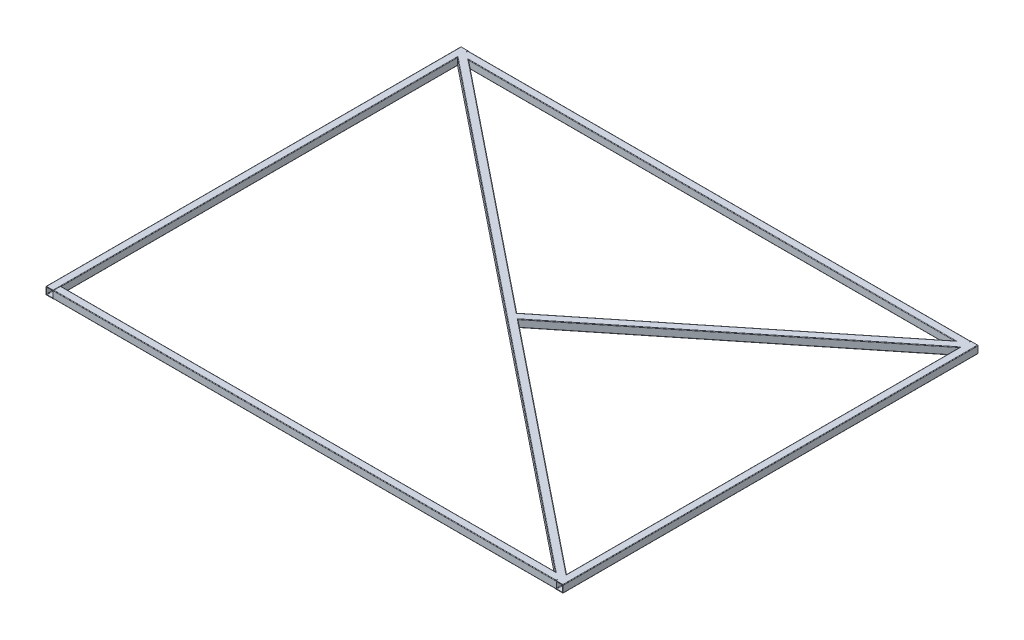
SolidWorks part; units mm, degrees
material "ASTM A500 Grade B"
ref_plane "Front Plane" through (0, 0, 0) normal (0, 0, 1) x (1, 0, 0)
ref_plane "Top Plane" through (0, 0, 0) normal (0, 1, 0) x (1, 0, 0)
ref_plane "Right Plane" through (0, 0, 0) normal (1, 0, 0) x (0, 0, -1)
sketch "Sketch1" plane through (0, 0, 0) normal (0, 1, 0) x (1, 0, 0)
  line L0 (1325, 0) -> (1325, -2125) construction
  line L1 (0, 0) -> (2650, 0)
  line L2 (0, 0) -> (0, -2125)
  line L3 (0, -2125) -> (2650, -2125)
  line L4 (2650, 0) -> (2650, -2125)
  line L5 (0, -1062.5) -> (2650, -1062.5) construction
  line L9 (0, 0) -> (2650, -2125) construction
  line L10 (2650, -2125) -> (2646.4748, -2133.2245) construction
  line L11 (1325, -1062.5) -> (1175.9048, -1248.4305) construction
  line L12 (2650, 0) -> (0, -2125) construction
  line L13 (1325, -1062.5) -> (1281.7828, -1008.6056) construction
  dimension "D1" = 2650
  dimension "D2" = 2125
sketch "Sketch2" plane through (0, 0, 0) normal (0, 0, 1) x (1, 0, 0)
  line L0 (5.3086, 16.1668) -> (32.7914, 16.1668)
  line L1 (2.54, 18.9354) -> (35.56, 18.9354)
  line L2 (0, 16.3954) -> (0, -16.6246)
  line L3 (2.54, -19.1646) -> (35.56, -19.1646)
  line L4 (38.1, 16.3954) -> (38.1, -16.6246)
  line L5 (35.3314, 13.6268) -> (35.3314, -13.856)
  line L6 (5.3086, -16.396) -> (32.7914, -16.396)
  line L7 (2.7686, 13.6268) -> (2.7686, -13.856)
  line L8 (2.7686, 16.1668) -> (2.7686, -16.396) construction
  line L9 (2.7686, -16.396) -> (35.3314, -16.396) construction
  line L10 (35.3314, 16.1668) -> (35.3314, -16.396) construction
  line L11 (38.1, 18.9354) -> (38.1, -19.1646) construction
  line L12 (0, -19.1646) -> (38.1, -19.1646) construction
  line L13 (0, 18.9354) -> (0, -19.1646) construction
  line L14 (0, 18.9354) -> (38.1, 18.9354) construction
  line L15 (2.7686, 16.1668) -> (35.3314, 16.1668) construction
  arc A0 (2.7686, -13.856) -> (5.3086, -16.396) centre (5.3086, -13.856) ccw
  arc A1 (32.7914, -16.396) -> (35.3314, -13.856) centre (32.7914, -13.856) ccw
  arc A2 (38.1, -16.6246) -> (35.56, -19.1646) centre (35.56, -16.6246) cw
  arc A3 (2.54, -19.1646) -> (0, -16.6246) centre (2.54, -16.6246) cw
  arc A4 (0, 16.3954) -> (2.54, 18.9354) centre (2.54, 16.3954) cw
  arc A5 (38.1, 16.3954) -> (35.56, 18.9354) centre (35.56, 16.3954) ccw
  arc A6 (35.3314, 13.6268) -> (32.7914, 16.1668) centre (32.7914, 13.6268) ccw
  arc A7 (2.7686, 13.6268) -> (5.3086, 16.1668) centre (5.3086, 13.6268) cw
  point P17 (38.1, -19.1646)
  dimension "D4" = 2.54
  dimension "D3" = 2.7686
extrude "Boss-Extrude1" add sketch "Sketch2" along normal up to vertex (2125 mm away) up to point (0, 0, 2125)
ref_plane "Plane1" through (1325, 0, 0) normal (-1, 0, 0) x (0, 0, 1)
mirror "Mirror2" about plane through (1325, 0, 0) normal (-1, 0, 0) of bodies 101
sketch "Sketch3" plane through (2611.9, 0, 0) normal (-1, 0, 0) x (0, 0, 1)
  line L0 (2125, -19.1646) -> (0, -19.1646) construction
  line L1 (2.54, 18.9354) -> (35.56, 18.9354)
  line L2 (0, 16.3954) -> (0, -16.6246)
  line L3 (2.54, -19.1646) -> (35.56, -19.1646)
  line L4 (38.1, 16.3954) -> (38.1, -16.6246)
  line L5 (5.3086, 16.1668) -> (32.7914, 16.1668)
  line L6 (35.3314, 13.6268) -> (35.3314, -13.856)
  line L7 (5.3086, -16.396) -> (32.7914, -16.396)
  line L8 (2.7686, 13.6268) -> (2.7686, -13.856)
  line L9 (38.1, 18.9354) -> (38.1, -19.1646) construction
  line L10 (0, -19.1646) -> (38.1, -19.1646) construction
  line L11 (2.7686, -16.396) -> (35.3314, -16.396) construction
  line L12 (35.3314, 16.1668) -> (35.3314, -16.396) construction
  line L13 (2.7686, 16.1668) -> (2.7686, -16.396) construction
  line L14 (0, 18.9354) -> (0, -19.1646) construction
  line L15 (2.7686, 16.1668) -> (35.3314, 16.1668) construction
  line L16 (0, 18.9354) -> (38.1, 18.9354) construction
  arc A0 (38.1, -16.6246) -> (35.56, -19.1646) centre (35.56, -16.6246) cw
  arc A1 (32.7914, -16.396) -> (35.3314, -13.856) centre (32.7914, -13.856) ccw
  arc A2 (5.3086, -16.396) -> (2.7686, -13.856) centre (5.3086, -13.856) cw
  arc A3 (2.54, -19.1646) -> (0, -16.6246) centre (2.54, -16.6246) cw
  arc A4 (2.7686, 13.6268) -> (5.3086, 16.1668) centre (5.3086, 13.6268) cw
  arc A5 (0, 16.3954) -> (2.54, 18.9354) centre (2.54, 16.3954) cw
  arc A6 (38.1, 16.3954) -> (35.56, 18.9354) centre (35.56, 16.3954) ccw
  arc A7 (35.3314, 13.6268) -> (32.7914, 16.1668) centre (32.7914, 13.6268) ccw
  point P14 (38.1, -19.1646)
  dimension "D3" = 2.54
  dimension "D2" = 2.7686
extrude "Boss-Extrude2" add sketch "Sketch3" along normal up to surface (2573.8 mm away) up to face at (38.1, -0.1146, 1062.5)
ref_plane "Plane2" through (0, 0, 1062.5) normal (0, 0, 1) x (1, 0, 0)
mirror "Mirror3" about plane through (0, 0, 1062.5) normal (0, 0, 1) of "Boss-Extrude2"
ref_plane "Plane8" through (1325, 0, 1062.5) normal (-0.7802, 0, -0.6256) x (-0.6256, 0, 0.7802)
sketch "Sketch8" plane through (1325, 0, 1062.5) normal (-0.7802, 0, -0.6256) x (-0.6256, 0, 0.7802)
  line L1 (-16.51, 18.9354) -> (16.51, 18.9354)
  line L2 (-19.05, 16.3954) -> (-19.05, -16.6246)
  line L3 (-16.51, -19.1646) -> (16.51, -19.1646)
  line L4 (19.05, 16.3954) -> (19.05, -16.6246)
  line L6 (16.2814, 13.6268) -> (16.2814, -13.856)
  line L7 (-13.7414, -16.396) -> (13.7414, -16.396)
  line L8 (-16.2814, 13.6268) -> (-16.2814, -13.856)
  line L9 (-13.7414, 16.1668) -> (13.7414, 16.1668)
  line L10 (-19.05, -19.1646) -> (19.05, -19.1646) construction
  line L11 (-19.05, 18.9354) -> (-19.05, -19.1646) construction
  line L12 (-16.2814, -16.396) -> (16.2814, -16.396) construction
  line L13 (-16.2814, 16.1668) -> (-16.2814, -16.396) construction
  line L14 (19.05, 18.9354) -> (19.05, -19.1646) construction
  line L15 (16.2814, 16.1668) -> (16.2814, -16.396) construction
  line L16 (-19.05, 18.9354) -> (19.05, 18.9354) construction
  line L17 (-16.2814, 16.1668) -> (16.2814, 16.1668) construction
  arc A0 (-16.51, -19.1646) -> (-19.05, -16.6246) centre (-16.51, -16.6246) cw
  arc A1 (-13.7414, -16.396) -> (-16.2814, -13.856) centre (-13.7414, -13.856) cw
  arc A2 (16.51, -19.1646) -> (19.05, -16.6246) centre (16.51, -16.6246) ccw
  arc A3 (13.7414, -16.396) -> (16.2814, -13.856) centre (13.7414, -13.856) ccw
  arc A4 (19.05, 16.3954) -> (16.51, 18.9354) centre (16.51, 16.3954) ccw
  arc A5 (16.2814, 13.6268) -> (13.7414, 16.1668) centre (13.7414, 13.6268) ccw
  arc A6 (-19.05, 16.3954) -> (-16.51, 18.9354) centre (-16.51, 16.3954) cw
  arc A7 (-16.2814, 13.6268) -> (-13.7414, 16.1668) centre (-13.7414, 13.6268) cw
  dimension "D4" = 2.54
  dimension "D2" = 19.05
  dimension "D3" = 2.7686
extrude "Boss-Extrude5" add sketch "Sketch8" against normal up to body and the other way up to body
ref_plane "Plane9" through (287.8812, 0, -230.8481) normal (0.7802, 0, -0.6256) x (-0.6256, 0, -0.7802)
sketch "Sketch9" plane through (287.8812, 0, -230.8481) normal (0.7802, 0, -0.6256) x (-0.6256, 0, -0.7802)
  line L1 (-1674.3293, 18.9354) -> (-1641.3093, 18.9354)
  line L2 (-1676.8693, 16.3954) -> (-1676.8693, -16.6246)
  line L3 (-1674.3293, -19.1646) -> (-1641.3093, -19.1646)
  line L4 (-1638.7693, 16.3954) -> (-1638.7693, -16.6246)
  line L5 (-1656.2303, -19.1646) -> (-1635.5732, -19.1646) construction
  line L6 (-1671.5607, 16.1668) -> (-1644.0779, 16.1668)
  line L7 (-1641.5379, 13.6268) -> (-1641.5379, -13.856)
  line L8 (-1671.5607, -16.396) -> (-1644.0779, -16.396)
  line L9 (-1674.1007, 13.6268) -> (-1674.1007, -13.856)
  line L10 (-1676.8693, -19.1646) -> (-1638.7693, -19.1646) construction
  line L11 (-1638.7693, 18.9354) -> (-1638.7693, -19.1646) construction
  line L12 (-1674.1007, -16.396) -> (-1641.5379, -16.396) construction
  line L13 (-1641.5379, 16.1668) -> (-1641.5379, -16.396) construction
  line L14 (-1676.8693, 18.9354) -> (-1638.7693, 18.9354) construction
  line L15 (-1674.1007, 16.1668) -> (-1641.5379, 16.1668) construction
  line L16 (-1676.8693, 18.9354) -> (-1676.8693, -19.1646) construction
  line L17 (-1674.1007, 16.1668) -> (-1674.1007, -16.396) construction
  arc A0 (-1641.3093, -19.1646) -> (-1638.7693, -16.6246) centre (-1641.3093, -16.6246) ccw
  arc A1 (-1644.0779, -16.396) -> (-1641.5379, -13.856) centre (-1644.0779, -13.856) ccw
  arc A2 (-1638.7693, 16.3954) -> (-1641.3093, 18.9354) centre (-1641.3093, 16.3954) ccw
  arc A3 (-1641.5379, 13.6268) -> (-1644.0779, 16.1668) centre (-1644.0779, 13.6268) ccw
  arc A4 (-1676.8693, -16.6246) -> (-1674.3293, -19.1646) centre (-1674.3293, -16.6246) ccw
  arc A5 (-1671.5607, -16.396) -> (-1674.1007, -13.856) centre (-1671.5607, -13.856) cw
  arc A6 (-1676.8693, 16.3954) -> (-1674.3293, 18.9354) centre (-1674.3293, 16.3954) cw
  arc A7 (-1674.1007, 13.6268) -> (-1671.5607, 16.1668) centre (-1671.5607, 13.6268) cw
  point P0 (-1657.8193, 0)
  point P17 (-1638.7693, -19.1646)
  dimension "D4" = 2.54
  dimension "D2" = 19.05
  dimension "D3" = 2.7686
ref_plane "Plane10" through (386.9603, 0, -310.2983) normal (0.7802, 0, -0.6256) x (-0.6256, 0, -0.7802)
sketch "Sketch11" plane through (386.9603, 0, -310.2983) normal (0.7802, 0, -0.6256) x (-0.6256, 0, -0.7802)
  line L1 (-1674.3293, 18.9354) -> (-1641.3093, 18.9354)
  line L2 (-1676.8693, 16.3954) -> (-1676.8693, -16.6246)
  line L3 (-1674.3293, -19.1646) -> (-1641.3093, -19.1646)
  line L4 (-1638.7693, 16.3954) -> (-1638.7693, -16.6246)
  line L6 (-1671.5607, 16.1668) -> (-1644.0779, 16.1668)
  line L7 (-1641.5379, 13.6268) -> (-1641.5379, -13.856)
  line L8 (-1671.5607, -16.396) -> (-1644.0779, -16.396)
  line L9 (-1674.1007, 13.6268) -> (-1674.1007, -13.856)
  line L10 (-1676.8693, -19.1646) -> (-1638.7693, -19.1646) construction
  line L11 (-1638.7693, 18.9354) -> (-1638.7693, -19.1646) construction
  line L12 (-1674.1007, -16.396) -> (-1641.5379, -16.396) construction
  line L13 (-1641.5379, 16.1668) -> (-1641.5379, -16.396) construction
  line L14 (-1676.8693, 18.9354) -> (-1638.7693, 18.9354) construction
  line L15 (-1674.1007, 16.1668) -> (-1641.5379, 16.1668) construction
  line L16 (-1676.8693, 18.9354) -> (-1676.8693, -19.1646) construction
  line L17 (-1674.1007, 16.1668) -> (-1674.1007, -16.396) construction
  arc A0 (-1641.3093, -19.1646) -> (-1638.7693, -16.6246) centre (-1641.3093, -16.6246) ccw
  arc A1 (-1644.0779, -16.396) -> (-1641.5379, -13.856) centre (-1644.0779, -13.856) ccw
  arc A2 (-1638.7693, 16.3954) -> (-1641.3093, 18.9354) centre (-1641.3093, 16.3954) ccw
  arc A3 (-1641.5379, 13.6268) -> (-1644.0779, 16.1668) centre (-1644.0779, 13.6268) ccw
  arc A4 (-1676.8693, -16.6246) -> (-1674.3293, -19.1646) centre (-1674.3293, -16.6246) ccw
  arc A5 (-1671.5607, -16.396) -> (-1674.1007, -13.856) centre (-1671.5607, -13.856) cw
  arc A6 (-1676.8693, 16.3954) -> (-1674.3293, 18.9354) centre (-1674.3293, 16.3954) cw
  arc A7 (-1674.1007, 13.6268) -> (-1671.5607, 16.1668) centre (-1671.5607, 13.6268) cw
  point P0 (-1657.8193, 0)
  point P17 (-1638.7693, -19.1646)
  dimension "D4" = 2.54
  dimension "D2" = 19.05
  dimension "D3" = 2.7686
extrude "Boss-Extrude7" add sketch "Sketch11" against normal up to body and the other way up to body
